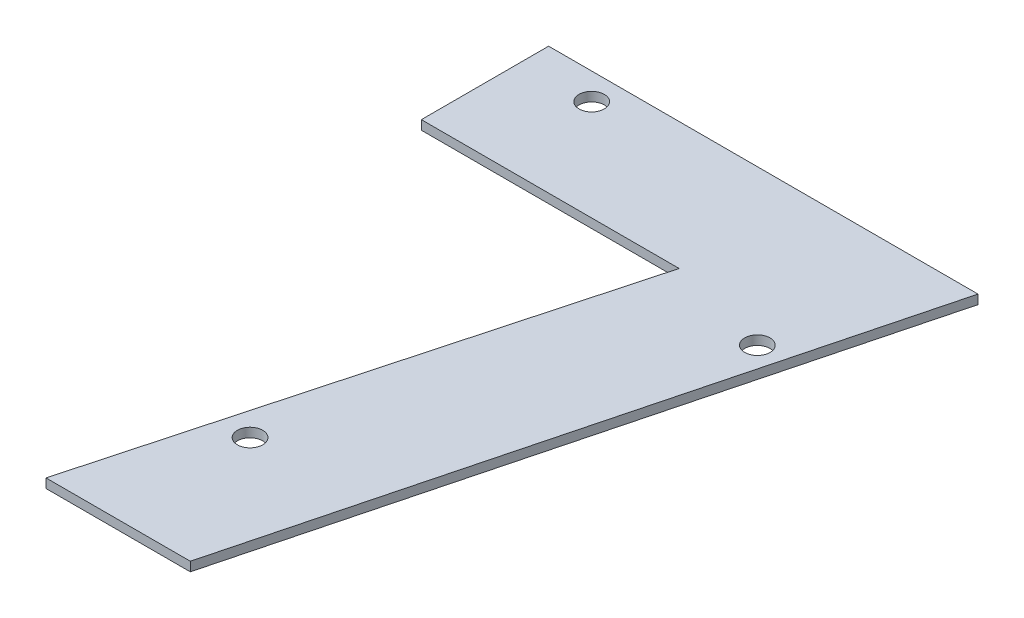
SolidWorks part; units mm, degrees
ref_plane "Front Plane" through (0, 0, 0) normal (0, 0, 1) x (1, 0, 0)
ref_plane "Top Plane" through (0, 0, 0) normal (0, 1, 0) x (1, 0, 0)
ref_plane "Right Plane" through (0, 0, 0) normal (1, 0, 0) x (0, 0, -1)
sketch "Sketch1" plane through (0, 0, 0) normal (0, 1, 0) x (1, 0, 0)
  line L0 (-32.8064, 51.9946) -> (60.5527, 51.9946)
  line L1 (60.5527, 51.9946) -> (25.225, -83.9464)
  line L2 (25.225, -83.9464) -> (-6.1499, -83.9464)
  line L3 (-6.1499, -83.9464) -> (23.25, 24.3237)
  line L4 (23.25, 24.3237) -> (-32.8064, 24.3237)
  line L5 (-32.8064, 24.3237) -> (-32.8064, 51.9946)
  dimension "D1" = 31.375
  dimension "D2" = 140.4564
  dimension "D3" = 93.3592
  dimension "D4" = 112.1908
  dimension "D5" = 56.0564
  dimension "D6" = 27.6708
extrude "Boss-Extrude1" add sketch "Sketch1" along normal blind 2
sketch "Sketch7" plane through (0, 0, 0) normal (0, 1, 0) x (1, 0, 0)
  circle A0 centre (-17.6754, 46.2308) radius 2.75
  circle A1 centre (46.1883, 18.3851) radius 2.75
  circle A2 centre (8.4312, -54.161) radius 2.75
  dimension "D1" = 5.5
  dimension "D2" = 5.5
  dimension "D3" = 5.5
extrude "Cut-Extrude1" cut sketch "Sketch7" along normal through all
